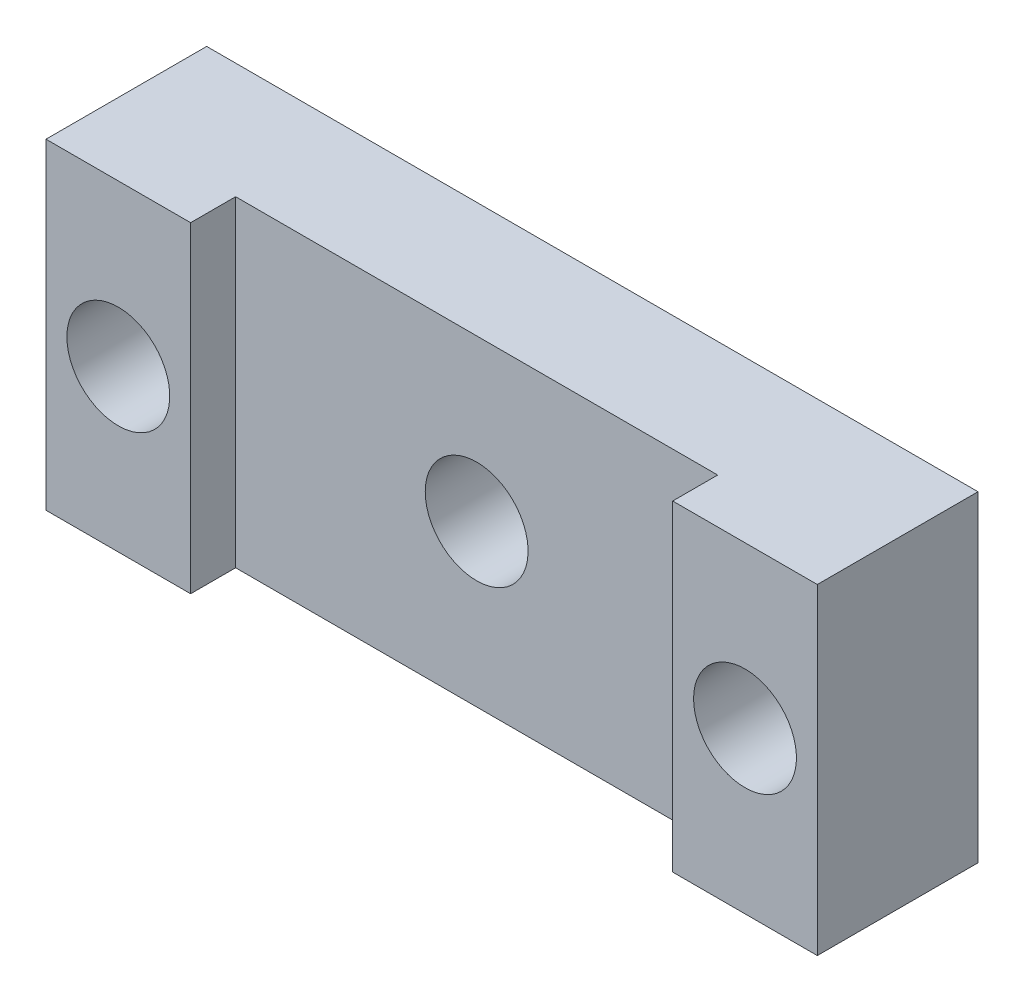
SolidWorks part; units mm, degrees
ref_plane "Front Plane" through (0, 0, 0) normal (0, 0, 1) x (1, 0, 0)
ref_plane "Top Plane" through (0, 0, 0) normal (0, 1, 0) x (1, 0, 0)
ref_plane "Right Plane" through (0, 0, 0) normal (1, 0, 0) x (0, 0, -1)
sketch "Sketch1" plane through (0, 0, 0) normal (0, 1, 0) x (1, 0, 0)
  line L0 (0, 0) -> (2.25, 0)
  line L1 (2.25, 0) -> (2.25, 0.7)
  line L2 (0, 0) -> (0, 2.5)
  line L3 (0, 2.5) -> (12, 2.5)
  line L4 (12, 0) -> (12, 2.5)
  line L5 (2.25, 0.7) -> (9.75, 0.7)
  line L6 (9.75, 0.7) -> (9.75, 0)
  line L7 (9.75, 0) -> (12, 0)
extrude "Boss-Extrude1" add sketch "Sketch1" along normal blind 5
hole_wizard "#97 (0.0059) Diameter Hole1" positions "Sketch3" profile "Sketch2" hole size "#97" standard "ANSI Inch"
sketch "Sketch3" plane through (0, 0, -2.5) normal (0, 0, -1) x (-1, 0, 0)
  line L1 (-12, 5) -> (-12, 0) construction
  line L2 (-12, 5) -> (0, 5) construction
  point P0 (-10.875, 2.5)
  dimension "D1" = 1.125
  dimension "D2" = 2.5
sketch "Sketch2" plane through (10.875, 2.5, -2.5) normal (1, 0, 0) x (0, 1, 0)
  line L0 (0, 0) -> (0, 3)
  line L1 (0, 3) -> (0.8, 3)
  line L2 (0.8, 3) -> (0.8, 0)
  line L5 (0.8, 0) -> (0, 0)
  line L10 (0, 3) -> (-0.8, 3) construction
  line L11 (0, -6.35) -> (0, 107.95) construction
  dimension "Hole Dia." = 1.6
  dimension "Hole Depth" = 3
  dimension "Drill Angle" = 180
ref_plane "Plane1" through (6, 0, 0) normal (1, 0, 0) x (0, 0, -1)
hole_wizard "M2x0.4 Tapped Hole1" positions "Sketch5" profile "Sketch4" tap size "M2x0.4" standard "ANSI Metric"
sketch "Sketch5" plane through (0, 0, -2.5) normal (0, 0, -1) x (-1, 0, 0)
  point P0 (-6, 2.5)
sketch "Sketch4" plane through (6, 2.5, -2.5) normal (1, 0, 0) x (0, 1, 0)
  line L0 (0, 0) -> (0, 5.6807)
  line L1 (0, 5.6807) -> (0.8, 5.2)
  line L2 (0.8, 5.2) -> (0.8, 0)
  line L5 (0.8, 0) -> (0, 0)
  line L10 (0, 5.6807) -> (-0.8, 5.2) construction
  line L11 (0, -6.35) -> (0, 107.95) construction
  dimension "Tap Drill Dia." = 1.6
  dimension "Tap Drill Depth" = 5.2
  dimension "Drill Angle" = 118
mirror "Mirror1" about plane through (6, 0, 0) normal (1, 0, 0) of "#97 (0.0059) Diameter Hole1"
